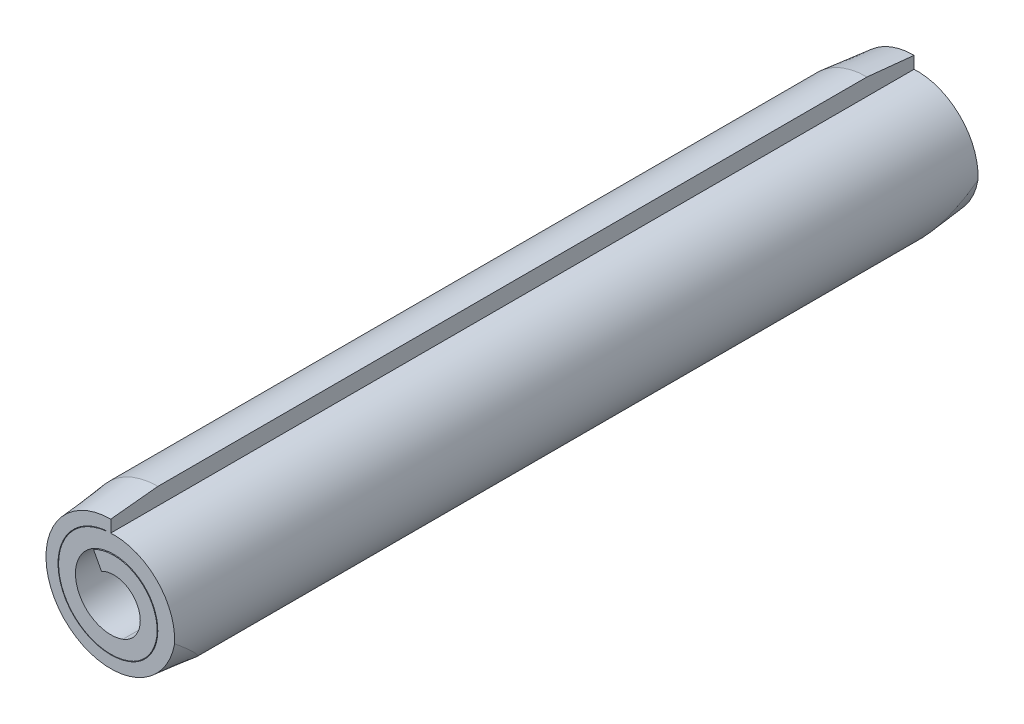
SolidWorks part; units mm, degrees
material "Alloy Steel"
ref_plane "Front Plane" through (0, 0, 0) normal (0, 0, 1) x (1, 0, 0)
ref_plane "Top Plane" through (0, 0, 0) normal (0, 1, 0) x (1, 0, 0)
ref_plane "Right Plane" through (0, 0, 0) normal (1, 0, 0) x (0, 0, -1)
sketch "Sketch1" plane through (0, 0, 0) normal (0, 0, 1) x (1, 0, 0)
  line L0 (0, 0) -> (0, 1.651) construction
  line L1 (0, 0.4127) -> (0, 0.8255) construction
  line L2 (0, 0.8255) -> (0, 1.2383) construction
  line L3 (0, 0.4127) -> (0, 0) construction
  line L4 (0, -0.4127) -> (0, 0) construction
  line L5 (0, -0.4127) -> (0, -0.8255) construction
  line L6 (0, -0.8255) -> (0, -1.2383) construction
  line L7 (0, 0) -> (-0.5647, 1.5514) construction
  line L8 (0, 0) -> (0.5647, -1.5514) construction
  circle A0 centre (0, 0) radius 1.651
  point P0 (0, -0.4127)
  point P3 (0, 0.4127)
  point P5 (0, 0.8255)
  point P6 (0, 1.2383)
  point P9 (0, -0.8255)
  point P12 (0, -1.2383)
  dimension "OD" = 3.302
  dimension "D2" = 1.651
  dimension "D3" = 0.4127
  dimension "D4" = 20
  dimension "D5" = 20
sketch "Sketch2" plane through (0, 0, 0) normal (0, 0, 1) x (1, 0, 0)
  line L0 (0, 0) -> (-0.5647, 1.5514) construction
  line L1 (0, 0) -> (0, 1.651) construction
  line L2 (0, 0) -> (0.5647, -1.5514) construction
  line L3 (0, 0) -> (-0.8255, 1.4298) construction
  arc A0 (0, 1.651) -> (0.5647, -1.5514) centre (0, 0) ccw
  arc A2 (0.5647, -1.5514) -> (-0.4235, 1.1636) centre (0.0706, -0.1939) ccw
  arc A3 (-0.4235, 1.1636) -> (0.4235, -1.1636) centre (0, 0) ccw
  arc A4 (0.4235, -1.1636) -> (-0.4089, 0.7083) centre (0.0723, -0.1987) ccw
  circle A5 centre (0, 0) radius 1.651 construction
  dimension "D1" = 20
  dimension "D2" = 10
extrude "Extrude-Thin1" add sketch "Sketch2" against normal mid plane 19.05 thin thin type one direction reverse wall 0.4004
sketch "Sketch3" plane through (0, 0, 0) normal (1, 0, 0) x (0, 0, -1)
  line L0 (-9.525, 1.651) -> (-9.525, 1.5367)
  line L1 (-9.525, 1.5367) -> (-8.4074, 1.651)
  line L2 (-8.4074, 1.651) -> (-9.525, 1.651)
  line L3 (0, 0) -> (-9.525, 0) construction
  line L4 (-9.525, 1.2507) -> (-9.525, -1.5514) construction
  line L5 (-8.4074, -1.651) -> (-9.525, -1.651) construction
  line L6 (-9.525, -1.5367) -> (-8.4074, -1.651) construction
  line L7 (-9.525, -1.651) -> (-9.525, -1.5367) construction
  line L8 (0, 0) -> (0, 1.651) construction
  line L9 (9.525, 1.651) -> (-9.525, 1.651) construction
  line L10 (8.4074, 1.651) -> (9.525, 1.651)
  line L11 (9.525, 1.5367) -> (8.4074, 1.651)
  line L12 (9.525, 1.651) -> (9.525, 1.5367)
  dimension "Chamfer Lenght" = 1.1176
  dimension "B" = 3.0734
revolve "Cut-Revolve1" cut sketch "Sketch3" angle 360 about L3
equation "\"D3@Sketch1\" = \"D2@Sketch1\"/4"
equation "\"D5@Extrude-Thin1\" = \"D3@Sketch1\"*.97"
